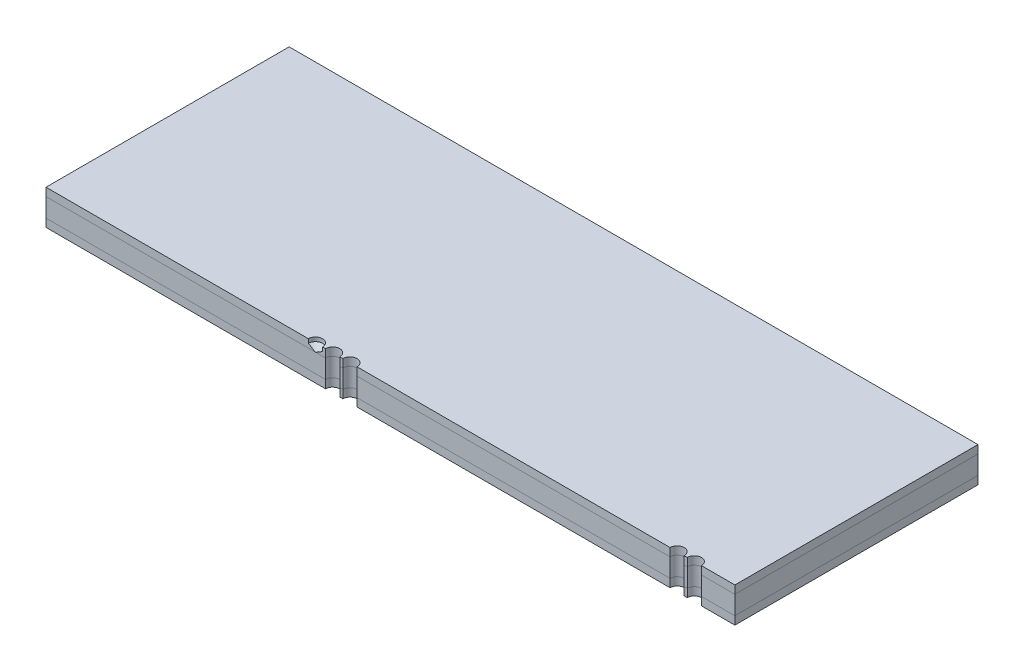
SolidWorks part; units mm, degrees
ref_plane "Front Plane" through (0, 0, 0) normal (0, 0, 1) x (1, 0, 0)
ref_plane "Top Plane" through (0, 0, 0) normal (0, 1, 0) x (1, 0, 0)
ref_plane "Right Plane" through (0, 0, 0) normal (1, 0, 0) x (0, 0, -1)
sketch "Sketch1" plane through (0, 0, 0) normal (0, 1, 0) x (1, 0, 0)
  line L1 (-85, 0) -> (85, 0)
  line L2 (-85, 0) -> (-85, 60)
  line L3 (-85, 60) -> (85, 60)
  line L4 (85, 0) -> (85, 60)
  dimension "D1" = 170
  dimension "D2" = 60
extrude "Boss-Extrude1" add sketch "Sketch1" along normal blind 2
sketch "Sketch2" plane through (0, 0, 0) normal (0, -1, 0) x (1, 0, 0)
  line L4 (-85, 0) -> (-85, -60)
  line L5 (-85, -60) -> (85, -60)
  line L6 (85, -60) -> (85, 0)
  line L7 (85, 0) -> (-85, 0)
  line L8 (-85, 0) -> (-85, -60)
  line L9 (-85, -60) -> (85, -60)
  line L10 (85, -60) -> (85, 0)
  line L11 (85, 0) -> (-85, 0)
  dimension "D1" = 0
extrude "Boss-Extrude2" add sketch "Sketch2" along normal blind 4.6 separate body
sketch "Sketch3" plane through (0, -4.6, 0) normal (0, -1, 0) x (1, 0, 0)
  line L4 (85, 0) -> (-85, 0)
  line L5 (-85, 0) -> (-85, -60)
  line L6 (-85, -60) -> (85, -60)
  line L7 (85, -60) -> (85, 0)
  line L8 (85, 0) -> (-85, 0)
  line L9 (-85, 0) -> (-85, -60)
  line L10 (-85, -60) -> (85, -60)
  line L11 (85, -60) -> (85, 0)
  dimension "D1" = 0
extrude "Boss-Extrude3" add sketch "Sketch3" along normal blind 2 separate body
sketch "Sketch4" plane through (0, 2, 0) normal (0, 1, 0) x (1, 0, 0)
  line L0 (-85, 0) -> (85, 0) construction
  line L1 (85, 0) -> (85, 60) construction
  circle A0 centre (75, 0) radius 1.75
  circle A1 centre (-10, 0) radius 1.75
  circle A2 centre (70.75, 0) radius 1.75
  circle A3 centre (-14.25, 0) radius 1.75
  point P6 (0, 0)
  dimension "D3" = 3.5
  dimension "D4" = 3.5
  dimension "D5" = 3.5
  dimension "D6" = 3.5
  dimension "D7" = 0.75
  dimension "D8" = 0.75
  dimension "D1" = 10
  dimension "D2" = 10
extrude "Cut-Extrude1" cut sketch "Sketch4" against normal through all
hole_wizard "Ø3.5 (3.5) Diameter Hole1" positions "Sketch6" profile "Sketch8" hole size "Ø3.5" standard "ISO"
sketch "Sketch6" plane through (0, 2, 0) normal (0, 1, 0) x (1, 0, 0)
  line L0 (-85, 0) -> (-16, 0) construction
  point P0 (-18.5, 0)
  dimension "D1" = 2.5
sketch "Sketch8" plane through (-18.5, 2, 0) normal (1, 0, 0) x (0, 0, 1)
  line L0 (0, 0) -> (0, 2.0515)
  line L1 (0, 2.0515) -> (1.75, 1)
  line L2 (1.75, 1) -> (1.75, 0)
  line L5 (1.75, 0) -> (0, 0)
  line L10 (0, 2.0515) -> (-1.75, 1) construction
  line L11 (0, -6.35) -> (0, 107.95) construction
  dimension "Hole Dia." = 3.5
  dimension "Hole Depth" = 1
  dimension "Drill Angle" = 118
mirror "Mirror1" [suppressed]
ref_plane "Plane2" through (0, 1, 0) normal (0, -1, 0) x (-1, 0, 0)
